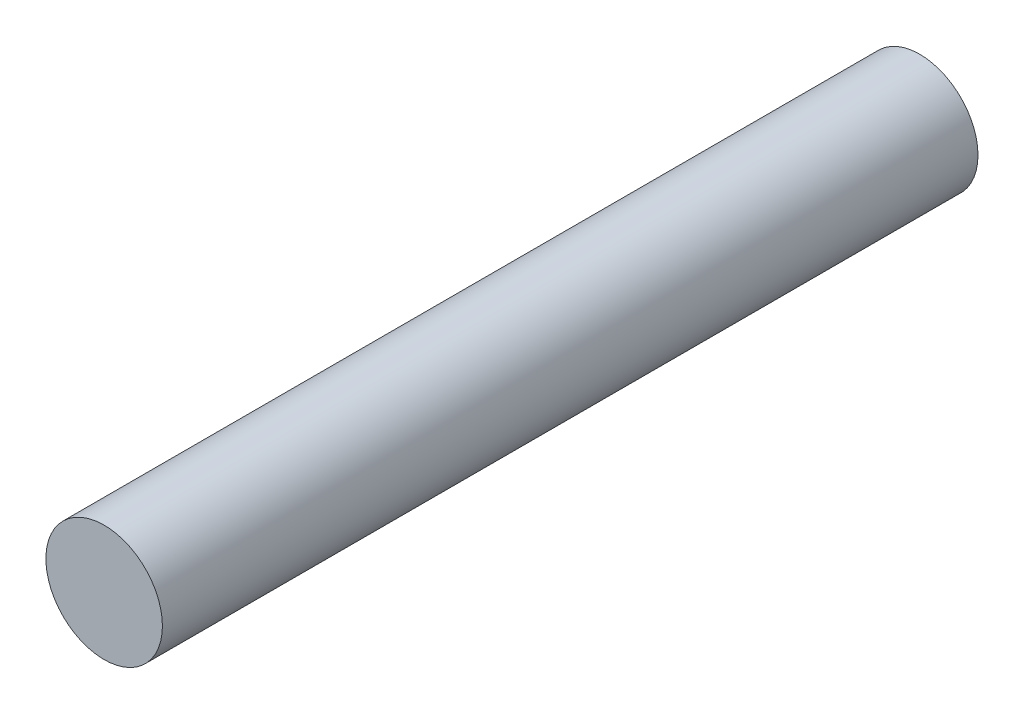
SolidWorks part; units mm, degrees
ref_plane "Front Plane" through (0, 0, 0) normal (0, 0, 1) x (1, 0, 0)
ref_plane "Top Plane" through (0, 0, 0) normal (0, 1, 0) x (1, 0, 0)
ref_plane "Right Plane" through (0, 0, 0) normal (1, 0, 0) x (0, 0, -1)
sketch "Sketch1" plane through (0, 0, 0) normal (0, 0, 1) x (1, 0, 0)
  circle A0 centre (0, 0) radius 2
  dimension "D1" = 4
extrude "Boss-Extrude1" add sketch "Sketch1" against normal mid plane 28
